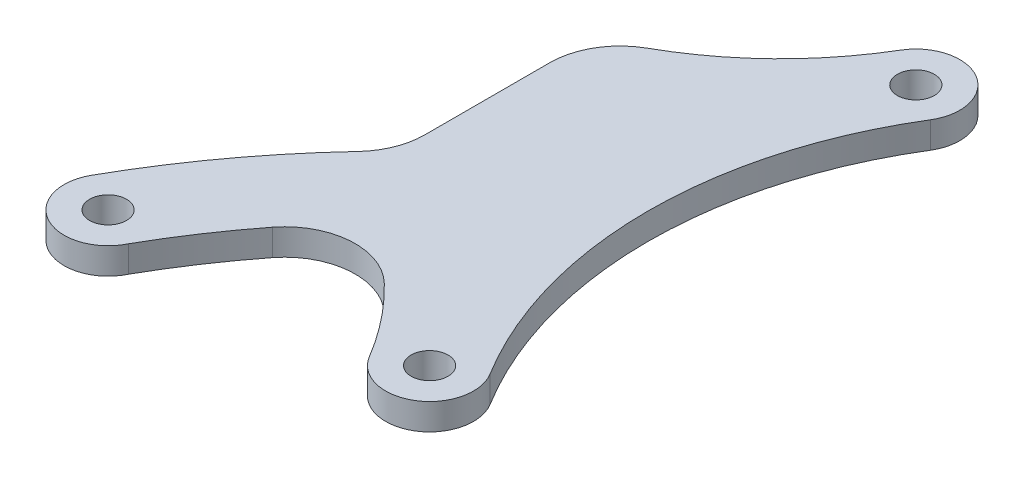
SolidWorks part; units mm, degrees
ref_plane "Front Plane" through (0, 0, 0) normal (0, 0, 1) x (1, 0, 0)
ref_plane "Top Plane" through (0, 0, 0) normal (0, 1, 0) x (1, 0, 0)
ref_plane "Right Plane" through (0, 0, 0) normal (1, 0, 0) x (0, 0, -1)
sketch "Sketch1" plane through (0, 0, 0) normal (0, 1, 0) x (1, 0, 0)
  line L0 (0, -14) -> (0, 14)
  circle A0 centre (23, -27.6464) radius 5
  circle A1 centre (23, 27.6464) radius 2.1
  circle A2 centre (23, -27.6464) radius 2.1
  circle A3 centre (23, 27.6464) radius 5
  arc A4 (18.7031, -30.203) -> (0, -14) centre (-15.0812, -50.3041) ccw
  arc A5 (18.7031, 30.203) -> (0, 14) centre (-15.0812, 50.3041) cw
  arc A6 (27.2602, -25.029) -> (27.2602, 25.029) centre (68, 0) cw
  arc A7 (-14.9841, -28.1449) -> (-5.946, -32.3595) centre (-10.6216, -30.5879) ccw
  circle A8 centre (-10.6216, -30.5879) radius 2.1
  arc A9 (-14.9841, -28.1449) -> (0, -8.3964) centre (63.2934, -71.9789) cw
  arc A10 (-6.1137, -32.7511) -> (5.6498, -16.9027) centre (63.2934, -71.9789) cw
  point P16 (20.186, 0)
  point P20 (0, 0)
extrude "Boss-Extrude1" add sketch "Sketch1" along normal blind 3
fillet "Fillet1" radius 8 3 edges at (5.6498, 1.5, 16.9027) (0, 1.5, -14) (0, 1.5, 8.3964)
